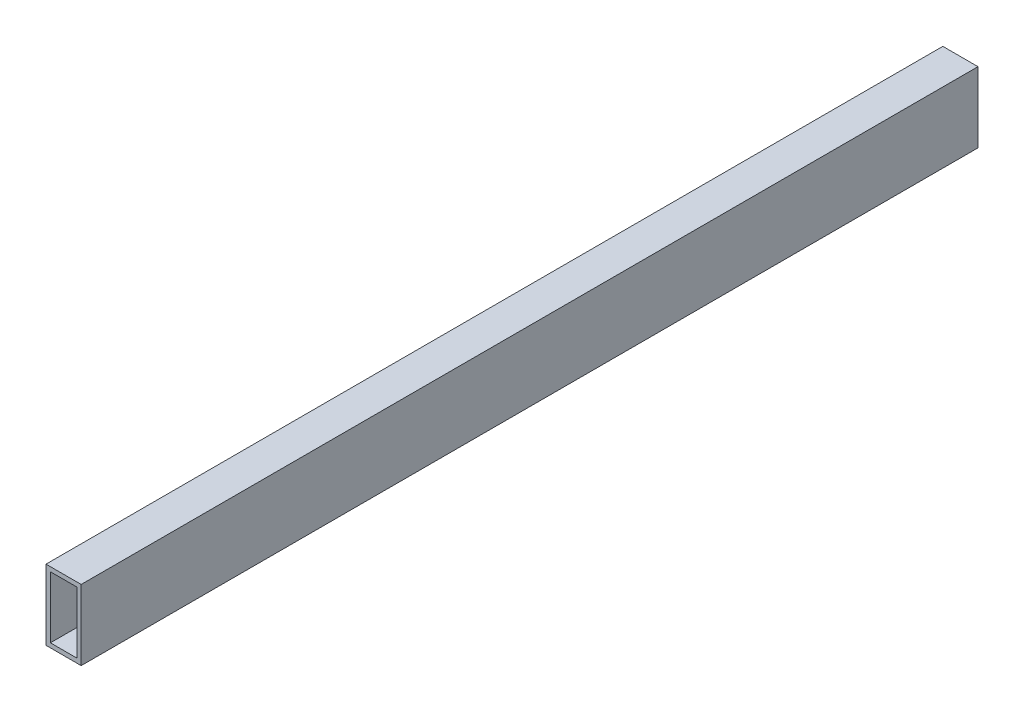
SolidWorks part; units mm, degrees
material "6061-T4 (SS)"
ref_plane "Front Plane" through (0, 0, 0) normal (0, 0, 1) x (1, 0, 0)
ref_plane "Top Plane" through (0, 0, 0) normal (0, 1, 0) x (1, 0, 0)
ref_plane "Right Plane" through (0, 0, 0) normal (1, 0, 0) x (0, 0, -1)
sketch "Sketch1" plane through (0, 0, 0) normal (0, 0, 1) x (1, 0, 0)
  line L0 (-9.525, 22.225) -> (9.525, 22.225)
  line L1 (-12.7, 25.4) -> (12.7, 25.4)
  line L2 (-12.7, 25.4) -> (-12.7, -25.4)
  line L3 (-12.7, -25.4) -> (12.7, -25.4)
  line L4 (12.7, 25.4) -> (12.7, -25.4)
  line L5 (-12.7, 25.4) -> (12.7, -25.4) construction
  line L6 (-12.7, -25.4) -> (12.7, 25.4) construction
  line L7 (9.525, 22.225) -> (9.525, -22.225)
  line L8 (-9.525, -22.225) -> (9.525, -22.225)
  line L9 (-9.525, 22.225) -> (-9.525, -22.225)
  point P0 (0, 0)
  dimension "D1" = 50.8
  dimension "D2" = 25.4
  dimension "D3" = 3.175
extrude "Boss-Extrude1" add sketch "Sketch1" along normal mid plane 647.7
